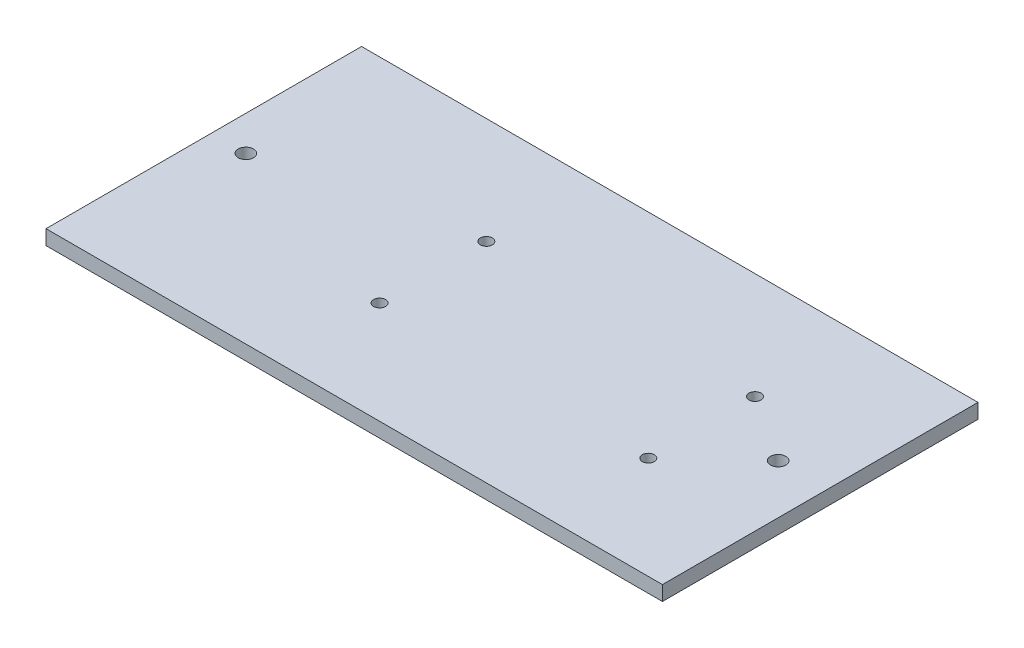
SolidWorks part; units mm, degrees
ref_plane "Front Plane" through (0, 0, 0) normal (0, 0, 1) x (1, 0, 0)
ref_plane "Top Plane" through (0, 0, 0) normal (0, 1, 0) x (1, 0, 0)
ref_plane "Right Plane" through (0, 0, 0) normal (1, 0, 0) x (0, 0, -1)
sketch "Sketch1" plane through (0, 0, 0) normal (0, 1, 0) x (1, 0, 0)
  line L0 (0, 34.0875) -> (0, -34.0875) construction
  line L1 (-66.5875, 34.0875) -> (66.5875, 34.0875)
  line L2 (-66.5875, 34.0875) -> (-66.5875, -34.0875)
  line L3 (-66.5875, -34.0875) -> (66.5875, -34.0875)
  line L4 (66.5875, 34.0875) -> (66.5875, -34.0875)
  line L5 (-66.5875, 34.0875) -> (66.5875, -34.0875) construction
  line L6 (-66.5875, -34.0875) -> (66.5875, 34.0875) construction
  line L7 (-59.0875, 26.5875) -> (55.9125, 26.5875) construction
  line L8 (-59.0875, 26.5875) -> (-59.0875, -23.4125) construction
  line L9 (-59.0875, -23.4125) -> (55.9125, -23.4125) construction
  line L10 (55.9125, 26.5875) -> (55.9125, -23.4125) construction
  line L11 (-66.5875, 0) -> (66.5875, 0) construction
  circle A1 centre (-59.0875, 1.5875) radius 1.65
  circle A2 centre (55.9125, 1.5875) radius 1.65
  point P0 (0, 0)
  point P6 (0, 0)
  dimension "D1" = 133.175
  dimension "D2" = 7.5
  dimension "D3" = 7.5
  dimension "D4" = 10.675
  dimension "D5" = 10.675
  dimension "D6" = 68.175
extrude "Boss-Extrude1" add sketch "Sketch1" along normal blind 3.175
sketch "Sketch2" plane through (0, 0, 0) normal (0, -1, 0) x (1, 0, 0)
  line L0 (66.5875, -34.0875) -> (-66.5875, -34.0875) construction
  line L1 (-16.6375, 11.9625) -> (41.4125, 11.9625) construction
  line L2 (-16.6375, 11.9625) -> (-16.6375, -11.0875) construction
  line L3 (-16.6375, -11.0875) -> (41.4125, -11.0875) construction
  line L4 (41.4125, 11.9625) -> (41.4125, -11.0875) construction
  line L5 (-16.6375, 11.9625) -> (41.4125, -11.0875) construction
  line L6 (-16.6375, -11.0875) -> (41.4125, 11.9625) construction
  line L8 (66.5875, 34.0875) -> (66.5875, -34.0875) construction
  circle A0 centre (-16.6375, 11.9625) radius 1.3
  circle A1 centre (-16.6375, -11.0875) radius 1.3
  circle A2 centre (41.4125, -11.0875) radius 1.3
  circle A3 centre (41.4125, 11.9625) radius 1.3
  point P0 (12.3875, 0.4375)
  dimension "D3" = 2.6
  dimension "D1" = 58.05
  dimension "D2" = 23.05
  dimension "D4" = 23
  dimension "D5" = 25.175
extrude "Cut-Extrude1" cut sketch "Sketch2" against normal up to surface (3.175 mm away) up to face at (-59.0875, 3.175, 0.0625)
